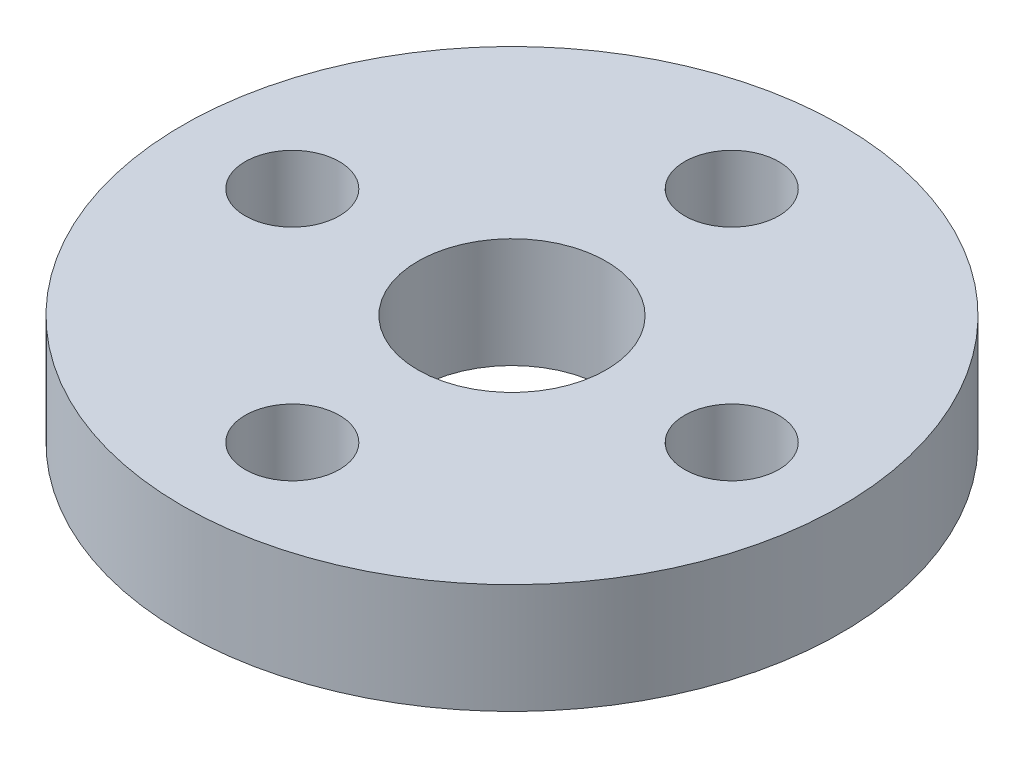
SolidWorks part; units mm, degrees
material "PE High Density"
ref_plane "Front Plane" through (0, 0, 0) normal (0, 0, 1) x (1, 0, 0)
ref_plane "Top Plane" through (0, 0, 0) normal (0, 1, 0) x (1, 0, 0)
ref_plane "Right Plane" through (0, 0, 0) normal (1, 0, 0) x (0, 0, -1)
sketch "Sketch1" plane through (0, 0, 0) normal (0, 1, 0) x (1, 0, 0)
  circle A0 centre (0, 0) radius 10.5
  dimension "D1" = 21
extrude "Boss-Extrude1" add sketch "Sketch1" along normal blind 3.5
sketch "Sketch2" plane through (0, 3.5, 0) normal (0, 1, 0) x (1, 0, 0)
  line L0 (0, 0) -> (0, 7) construction
  circle A0 centre (0, 0) radius 3
  circle A1 centre (0, 7) radius 1.5
  circle A2 centre (7, 0) radius 1.5
  circle A3 centre (0, -7) radius 1.5
  circle A4 centre (-7, 0) radius 1.5
  point P14 (0, 0)
  dimension "D1" = 4
  dimension "D2" = 6
  dimension "D3" = 7
extrude "Cut-Extrude1" cut sketch "Sketch2" against normal blind 10.2
